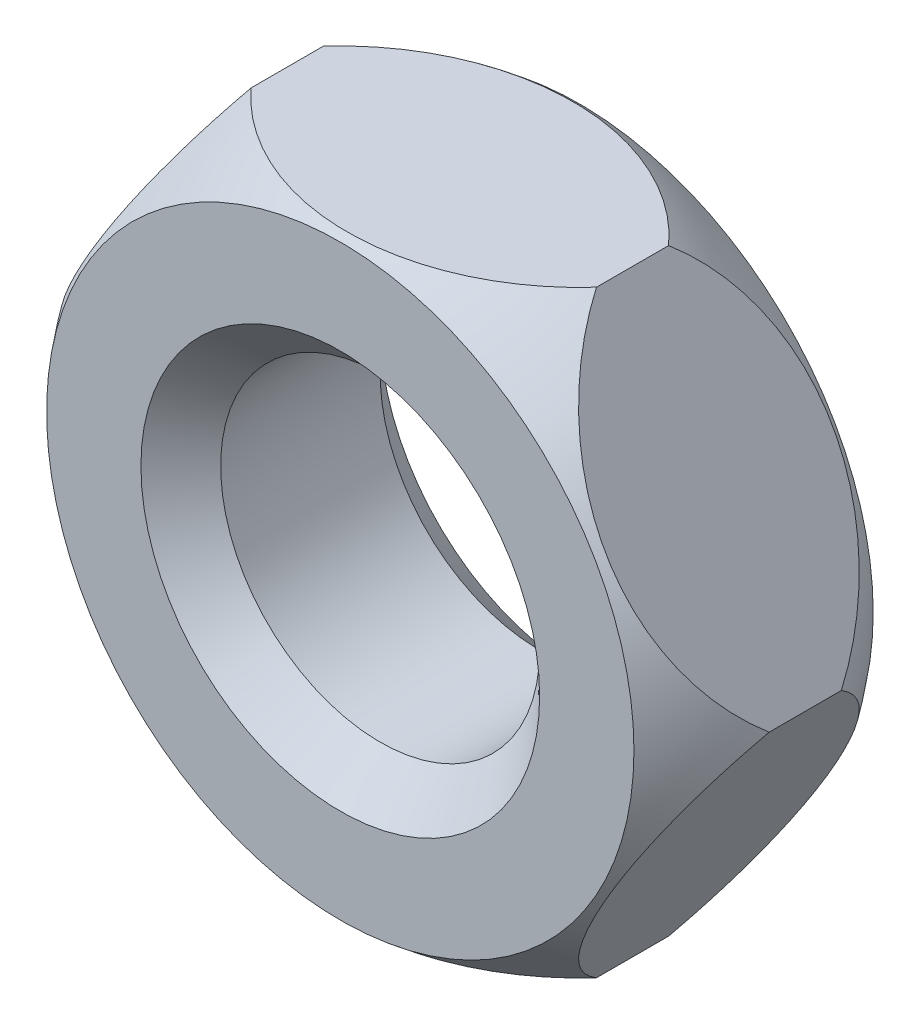
SolidWorks part; units mm, degrees
material "Phosphor bronze 10% D, UNS C52400"
ref_plane "Front Plane" through (0, 0, 0) normal (0, 0, 1) x (1, 0, 0)
ref_plane "Top Plane" through (0, 0, 0) normal (0, 1, 0) x (1, 0, 0)
ref_plane "Right Plane" through (0, 0, 0) normal (1, 0, 0) x (0, 0, -1)
sketch "Sketch1" plane through (0, 0, 0) normal (0, 0, 1) x (1, 0, 0)
  line L1 (4.3301, 0) -> (2.1651, 3.75)
  line L2 (2.1651, 3.75) -> (-2.1651, 3.75)
  line L3 (-2.1651, 3.75) -> (-4.3301, 0)
  line L4 (-4.3301, 0) -> (-2.1651, -3.75)
  line L5 (-2.1651, -3.75) -> (2.1651, -3.75)
  line L6 (2.1651, -3.75) -> (4.3301, 0)
  circle A0 centre (0, 0) radius 2
  circle A1 centre (0, 0) radius 3.75 construction
  point P3 (0, 0)
  dimension "D1" = 4
  dimension "D2" = 7.5
extrude "Boss-Extrude1" add sketch "Sketch1" along normal blind 3
sketch "Sketch2" plane through (0, 0, 0) normal (0, 1, 0) x (1, 0, 0)
  line L0 (-4.3301, -1.9526) -> (4.3301, -1.9526) construction
  line L1 (-4.3301, -3) -> (-4.3301, 0) construction
  line L2 (4.3301, -3) -> (4.3301, 0) construction
  line L3 (0, -1.9526) -> (0, -4.75) construction
  line L4 (-4.3301, -1.9526) -> (-6.4153, -1.9526)
  line L5 (0, -4.75) -> (0, -6.7059)
  arc A0 (-4.3301, -1.9526) -> (0, -4.75) centre (0, 0) ccw
  arc A1 (-6.4153, -1.9526) -> (0, -6.7059) centre (0, 0) ccw
  dimension "D1" = 9.5
revolve "Cut-Revolve1" cut sketch "Sketch2" angle 360 about L3
ref_plane "Plane1" through (0, 0, 1.5) normal (0, 0, -1) x (-1, 0, 0)
mirror "Mirror1" about plane through (0, 0, 1.5) normal (0, 0, -1) of "Cut-Revolve1"
chamfer "Chamfer1" distance 0.5 angle 45 2 edges at (2, 0, 0) (2, 0, 3)
